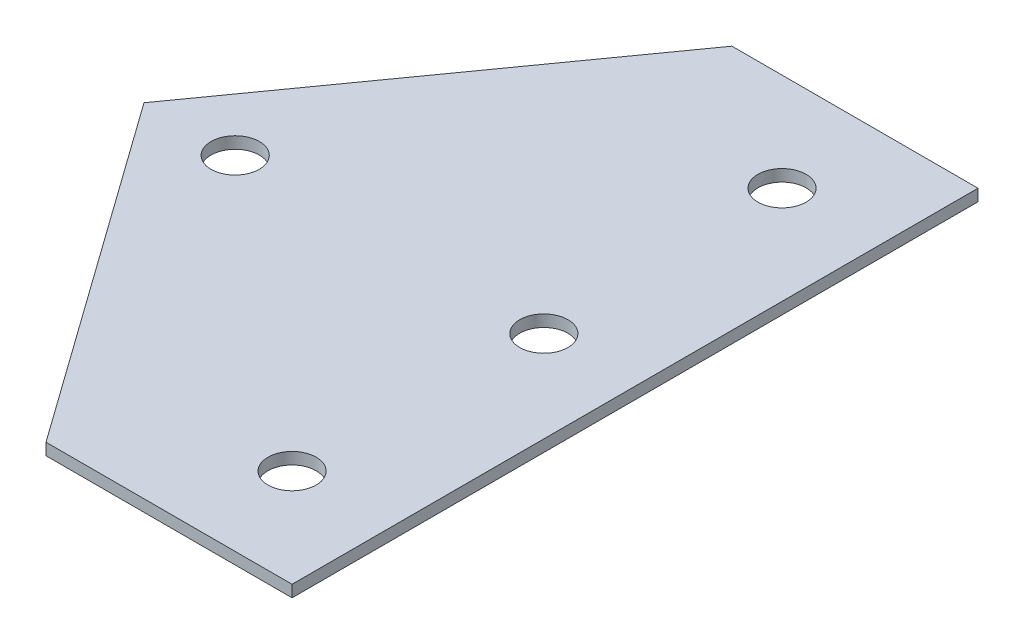
SolidWorks part; units mm, degrees
ref_plane "Front Plane" through (0, 0, 0) normal (0, 0, 1) x (1, 0, 0)
ref_plane "Top Plane" through (0, 0, 0) normal (0, 1, 0) x (1, 0, 0)
ref_plane "Right Plane" through (0, 0, 0) normal (1, 0, 0) x (0, 0, -1)
sketch "Sketch1" plane through (0, 0, 0) normal (0, 1, 0) x (1, 0, 0)
  line L0 (-63.7792, -177.8) -> (-190.7792, 0)
  line L5 (63.7792, -177.8) -> (-63.7792, -177.8)
  line L6 (63.7792, -177.8) -> (63.7792, 177.8)
  line L7 (63.7792, 177.8) -> (-63.7792, 177.8)
  line L9 (63.7792, -177.8) -> (-63.7792, 177.8) construction
  line L10 (63.7792, 177.8) -> (-63.7792, -177.8) construction
  line L11 (-190.7792, 0) -> (-63.7792, 177.8)
  line L13 (-63.5, -127.2792) -> (-190.7792, 0) construction
  point P0 (0, 0)
  point P5 (-149.6311, 8.8594)
  point P7 (-139.7, 0)
  point P10 (-63.5, 48.7717)
  point P11 (0, 0)
  point P13 (-190.7792, 0)
  dimension "D1" = 355.6
extrude "Boss-Extrude1" add sketch "Sketch1" along normal blind 6.096
sketch "Sketch3" plane through (0, 6.096, 0) normal (0, 1, 0) x (1, 0, 0)
  circle A4 centre (-143.5, 0) radius 12.5 construction
  circle A5 centre (16.5, 0) radius 12.5 construction
  circle A6 centre (-143.5, 0) radius 12.5
  circle A7 centre (16.5, 0) radius 12.5
extrude "Cut-Extrude1" cut sketch "Sketch3" against normal blind 44.45
sketch "Sketch4" plane through (0, 0, 0) normal (0, -1, 0) x (1, 0, 0)
  line L0 (63.7792, 0) -> (0, 0) construction
  line L1 (63.7792, 177.8) -> (63.7792, -177.8) construction
  line L2 (12.9792, 127) -> (63.7792, 127) construction
  line L3 (12.9792, 127) -> (12.9792, 177.8) construction
  line L4 (-63.7792, 177.8) -> (63.7792, 177.8) construction
  circle A0 centre (12.9792, 127) radius 12.5
  circle A1 centre (12.9792, -127) radius 12.5
  dimension "D2" = 25
  dimension "D1" = 50.8
extrude "Cut-Extrude2" cut sketch "Sketch4" against normal up to surface (6.096 mm away) up to face at (-143.5, 6.096, 12.5)
